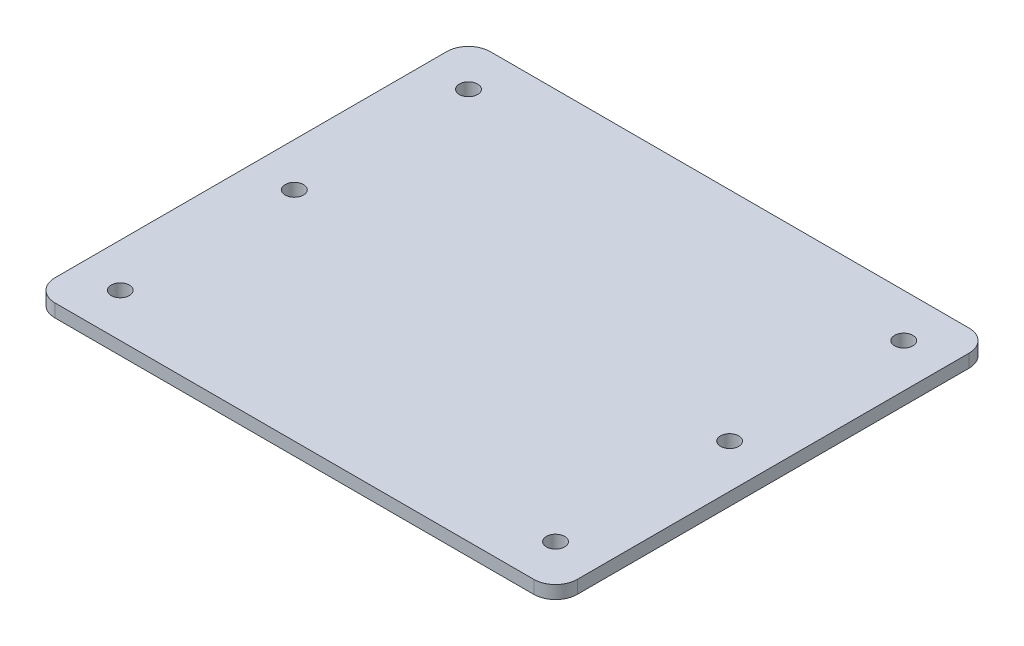
SolidWorks part; units mm, degrees
material "Thornel Mat VMA"
ref_plane "前视基准面" through (0, 0, 0) normal (0, 0, 1) x (1, 0, 0)
ref_plane "上视基准面" through (0, 0, 0) normal (0, 1, 0) x (1, 0, 0)
ref_plane "右视基准面" through (0, 0, 0) normal (1, 0, 0) x (0, 0, -1)
sketch "草图1" plane through (0, 0, 0) normal (0, 1, 0) x (1, 0, 0)
  line L1 (-60, 50) -> (60, 50)
  line L2 (-60, 50) -> (-60, -50)
  line L3 (-60, -50) -> (60, -50)
  line L4 (60, 50) -> (60, -50)
  line L5 (-60, 50) -> (60, -50) construction
  line L6 (-60, -50) -> (60, 50) construction
  point P0 (0, 0)
  dimension "D1" = 100
  dimension "D2" = 120
extrude "凸台-拉伸1" add sketch "草图1" along normal blind 3
fillet "圆角1" radius 5 4 edges at (-60, 1.5, 50) (60, 1.5, 50) (60, 1.5, -50) (-60, 1.5, -50)
ref_plane "基准面3" through (0, 0, 0) normal (1, 0, 0) x (0, 0, -1)
sketch "草图4" plane through (0, 3, 0) normal (0, 1, 0) x (1, 0, 0)
  line L0 (55, 50) -> (-55, 50) construction
  line L1 (0, -1.65) -> (0, 1.65) construction
  circle A0 centre (50, 40) radius 2.1
  dimension "D1" = 4.2
  dimension "D2" = 10
  dimension "D3" = 50
extrude "切除-拉伸2" cut sketch "草图4" against normal through all
pattern_linear "阵列(线性)1" count 3 spacing 40 along (0, 0, 1) of "切除-拉伸2"
mirror "镜向1" about plane through (0, 0, 0) normal (1, 0, 0) of "阵列(线性)1", "切除-拉伸2"
